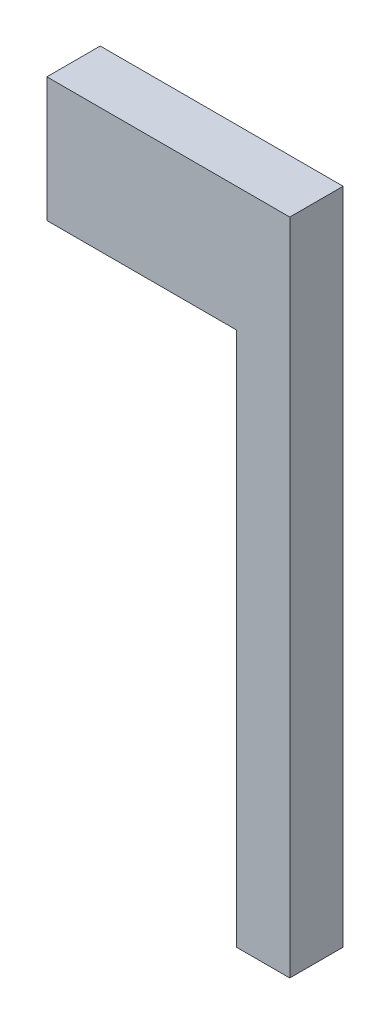
SolidWorks part; units mm, degrees
ref_plane "Front Plane" through (0, 0, 0) normal (0, 0, 1) x (1, 0, 0)
ref_plane "Top Plane" through (0, 0, 0) normal (0, 1, 0) x (1, 0, 0)
ref_plane "Right Plane" through (0, 0, 0) normal (1, 0, 0) x (0, 0, -1)
sketch "Sketch1" plane through (0, 0, 0) normal (0, 0, 1) x (1, 0, 0)
  line L0 (-10.5767, -18.9242) -> (-10.5767, -11.9242)
  line L1 (-10.5767, -11.9242) -> (3.0833, -11.9242)
  line L5 (-10.5767, -18.9242) -> (0.0833, -18.9242)
  line L8 (0.0833, -18.9242) -> (0.0833, -48.9842)
  line L19 (0.0833, -48.9842) -> (3.0833, -48.9842)
  line L20 (3.0833, -48.9842) -> (3.0833, -11.9242)
  dimension "D1" = 13.66
  dimension "D2" = 30.06
  dimension "D3" = 3
  dimension "D5" = 7
extrude "Boss-Extrude2" add sketch "Sketch1" along normal blind 3
